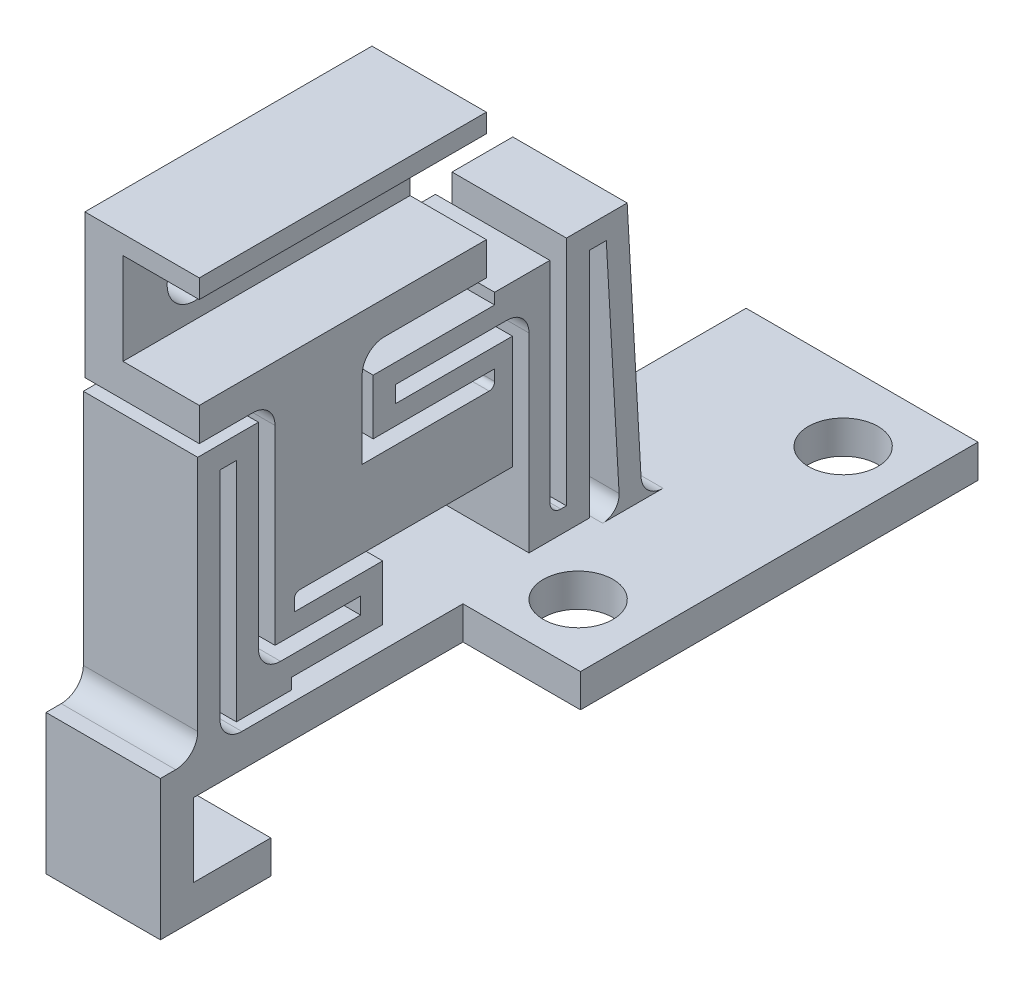
SolidWorks part; units mm, degrees
ref_plane "Front Plane" through (0, 0, 0) normal (0, 0, 1) x (1, 0, 0)
ref_plane "Top Plane" through (0, 0, 0) normal (0, 1, 0) x (1, 0, 0)
ref_plane "Right Plane" through (0, 0, 0) normal (1, 0, 0) x (0, 0, -1)
sketch "Sketch1" plane through (0, 0, 0) normal (1, 0, 0) x (0, 0, -1)
  line L0 (3.7437, -1.0669) -> (8.3687, -1.0669)
  line L1 (-4.6313, -1.0669) -> (-2.2011, -1.0669)
  line L2 (-4.6313, -1.0669) -> (-4.6313, 5.4331)
  line L3 (-4.6313, 5.4331) -> (8.3687, 5.4331)
  line L4 (8.3687, -1.0669) -> (8.3687, 5.4331)
  line L6 (-1.2011, -2.0669) -> (-1.2011, -10.6919)
  line L8 (2.7437, -2.0669) -> (2.7437, -5.5669)
  line L13 (-0.0761, -9.0669) -> (9.5489, -9.0669)
  line L14 (8.7437, -5.3169) -> (8.7437, -4.8169)
  line L16 (9.5489, -9.0669) -> (9.5489, -3.9419)
  line L17 (3.2437, -2.3169) -> (3.2437, -4.8169)
  line L20 (8.7437, -4.8169) -> (3.2437, -4.8169)
  line L25 (4.2437, -3.9419) -> (4.2437, -3.1919)
  line L26 (3.2437, -2.3169) -> (8.7437, -2.3169)
  line L28 (4.2437, -3.1919) -> (9.2989, -3.1919)
  line L32 (8.7437, -2.3169) -> (8.7437, -1.8169)
  line L33 (8.7437, -1.8169) -> (11.2437, -1.8169)
  line L35 (-1.2011, -10.6919) -> (2.6739, -10.6919)
  line L36 (2.6739, -10.6919) -> (2.6739, -11.4419)
  line L37 (2.6739, -11.4419) -> (-0.9511, -11.4419)
  line L40 (-2.9511, -12.8169) -> (-0.4511, -12.8169)
  line L41 (-0.4511, -12.8169) -> (-0.4511, -12.3169)
  line L42 (-0.4511, -12.3169) -> (3.6739, -12.3169)
  line L43 (3.6739, -12.3169) -> (3.6739, -9.8169)
  line L44 (3.6739, -9.8169) -> (-0.3261, -9.8169)
  line L45 (-0.3261, -9.8169) -> (-0.3261, -9.3169)
  line L48 (-1.9511, -10.4419) -> (-1.9511, -1.5669)
  line L50 (-2.9511, -12.8169) -> (-2.9511, -2.5669)
  line L51 (-1.9511, -1.5669) -> (-4.7011, -1.5669)
  line L53 (-2.9511, -2.5669) -> (-3.7011, -2.5669)
  line L56 (10.2989, -4.1919) -> (10.2989, -12.8169)
  line L58 (11.2437, -1.8169) -> (11.2437, -11.3169)
  line L59 (10.2989, -12.8169) -> (13.0489, -12.8169)
  line L61 (11.2437, -11.8169) -> (11.9937, -11.8169) construction
  line L65 (13.0489, -12.8169) -> (13.0489, -2.3169)
  line L67 (11.9937, -11.8169) -> (11.9937, -1.3169)
  line L69 (-4.7011, -1.5669) -> (-4.7011, -12.3169)
  line L71 (-3.7011, -2.5669) -> (-3.7011, -12.3169)
  line L72 (-4.7011, -13.3169) -> (-5.7011, -13.3169) construction
  line L76 (13.0489, -2.3169) -> (13.7989, -2.3169)
  line L78 (11.9937, -1.3169) -> (14.7437, -1.3169)
  line L80 (-4.6313, -14.8169) -> (15.4255, -14.8169)
  line L82 (13.63, -13.3169) -> (-2.7011, -13.3169)
  line L84 (4.2437, -3.9419) -> (9.5489, -3.9419)
  line L94 (8.4937, -5.5669) -> (2.7437, -5.5669)
  line L95 (13.7989, -2.3169) -> (14.3788, -12.5244)
  line L96 (4.2437, -2.3169) -> (4.2437, -3.1919) construction
  line L97 (4.2437, -3.9419) -> (4.2437, -4.8169) construction
  line L98 (2.6739, -9.8169) -> (2.6739, -10.6919) construction
  line L99 (2.6739, -11.4419) -> (2.6739, -12.3169) construction
  line L100 (8.7437, -4.8169) -> (8.7437, -5.5669) construction
  line L101 (-0.3261, -9.0669) -> (-0.3261, -9.8169)
  line L102 (14.7437, -1.3169) -> (15.4255, -13.3169)
  line L103 (11.9937, -11.8169) -> (11.7437, -11.8169)
  line L104 (-3.3261, -1.5669) -> (-3.3261, -2.5669) construction
  line L105 (15.4255, -13.3169) -> (15.4255, -14.8169)
  line L106 (-3.7011, -2.5669) -> (-4.7011, -2.5669) construction
  line L107 (-2.9511, -2.5669) -> (-1.9511, -2.5669) construction
  line L108 (-3.3261, -1.0669) -> (-3.3261, -1.5669) construction
  line L109 (3.2437, -3.5669) -> (2.7437, -3.5669) construction
  line L110 (3.6739, -12.3169) -> (3.6739, -13.3169) construction
  line L111 (-4.6313, -14.8169) -> (-4.8913, -14.8169)
  line L112 (-4.8913, -14.8169) -> (-4.8913, -18.1469)
  line L113 (-4.8913, -18.1469) -> (-1.3913, -18.1469)
  line L114 (-1.3913, -18.1469) -> (-1.3913, -19.6469)
  line L115 (-1.3913, -19.6469) -> (-6.3913, -19.6469)
  line L116 (-6.3913, -19.6469) -> (-6.3913, -13.3169)
  line L117 (-6.3913, -13.3169) -> (-5.7011, -13.3169)
  arc A0 (3.7437, -1.0669) -> (2.7437, -2.0669) centre (3.7437, -2.0669) ccw
  arc A1 (-2.2011, -1.0669) -> (-1.2011, -2.0669) centre (-2.2011, -2.0669) cw
  arc A2 (9.2989, -3.1919) -> (10.2989, -4.1919) centre (9.2989, -4.1919) cw
  arc A3 (-0.9511, -11.4419) -> (-1.9511, -10.4419) centre (-0.9511, -10.4419) cw
  arc A4 (-0.3261, -9.3169) -> (-0.0761, -9.0669) centre (-0.0761, -9.3169) cw
  arc A5 (8.7437, -5.3169) -> (8.4937, -5.5669) centre (8.4937, -5.3169) cw
  arc A6 (-2.7011, -13.3169) -> (-3.7011, -12.3169) centre (-2.7011, -12.3169) cw
  arc A7 (11.2437, -11.3169) -> (11.7437, -11.8169) centre (11.7437, -11.3169) ccw
  arc A10 (-5.7011, -13.3169) -> (-4.7011, -12.3169) centre (-5.7011, -12.3169) ccw
  arc A11 (14.3788, -12.5244) -> (13.63, -13.3169) centre (13.63, -12.5669) cw
  point P27 (14.4239, -13.3169)
  dimension "D4" = 1
  dimension "D14" = 0.25
  dimension "D18" = 1
  dimension "D20" = 0.5
  dimension "D21" = 0.75
  dimension "D2" = 13
  dimension "D3" = 6.5
  dimension "D5" = 13.75
  dimension "D6" = 20.25
  dimension "D13" = 1.5
  dimension "D25" = 5.5
  dimension "D27" = 2.5
  dimension "D32" = 10.75
  dimension "D33" = 0.875
  dimension "D37" = 0.5
  dimension "D39" = 2.5
  dimension "D41" = 4.125
  dimension "D42" = 1
  dimension "D11" = 0.75
  dimension "D17" = 1
  dimension "D12" = 1.25
  dimension "D15" = 11.75
  dimension "D16" = 1
  dimension "D22" = 0.75
  dimension "D7" = 11.5
  dimension "D8" = 2
  dimension "D9" = 2.75
  dimension "D19" = 93.252
  dimension "D23" = 1
  dimension "D26" = 3.33
  dimension "D28" = 1.5
  dimension "D29" = 1.5
  dimension "D30" = 5
  dimension "D31" = 0.75
  dimension "D10" = 1
extrude "Flexure Boss" add sketch "Sketch1" along normal blind 5.18
sketch "Sketch2" plane through (0, -14.8169, 0) normal (0, -1, 0) x (1, 0, 0)
  line L0 (0, 4.8913) -> (0, -15.4255) construction
  line L4 (-5.32, -7.3096) -> (-5.32, -25.3096)
  line L6 (5.18, 4.8913) -> (5.18, -15.4255) construction
  line L7 (-5.32, -25.3096) -> (5.18, -25.3096)
  line L12 (-5.32, -7.3096) -> (5.18, -7.3096)
  line L13 (5.18, -7.3096) -> (5.18, -25.3096)
  line L14 (5.18, 6.3913) -> (0, 6.3913) construction
  circle A0 centre (-2.435, -10.0887) radius 1.575
  circle A1 centre (-2.435, -22.0887) radius 1.575
  dimension "D1" = 16.48
  dimension "D2" = 5.32
  dimension "D3" = 12
  dimension "D4" = 3.15
  dimension "D5" = 2.435
  dimension "D6" = 18
  dimension "D8" = 7.3096
extrude "Mounting Plate Boss" add sketch "Sketch2" against normal blind 1.5
sketch "Sketch7" plane through (0, 0, 0) normal (-1, 0, 0) x (0, 0, 1)
  line L0 (-8.3687, 0.4331) -> (4.6313, 0.4331)
  line L1 (4.6313, 4.5831) -> (4.6313, 0.4331)
  line L2 (4.6313, 4.5831) -> (-8.3687, 4.5831)
  line L6 (-8.3687, 4.5831) -> (-8.3687, 0.4331)
  line L7 (4.6313, -1.0669) -> (4.6313, 5.4331) construction
  line L8 (-8.3687, -1.0669) -> (-8.3687, 5.4331) construction
  dimension "D1" = 1.5
  dimension "D2" = 4.15
extrude "Dovetail Connection Cut" cut sketch "Sketch7" against normal blind 3.455
hole_wizard "M3x0.5 Tapped Hole1" positions "Sketch11" profile "Sketch12" tap size "M3x0.5" standard "ANSI Metric" end condition up to next
sketch "Sketch11" plane through (5.18, 0, 0) normal (1, 0, 0) x (0, 0, -1)
  line L0 (-4.6313, 5.4331) -> (8.3687, 5.4331) construction
  line L1 (-4.6313, -1.0669) -> (-4.6313, 5.4331) construction
  line L2 (8.3687, -1.0669) -> (8.3687, 5.4331) construction
  point P0 (-1.3813, 2.4331)
  point P2 (5.1187, 2.4331)
  dimension "D1" = 3
  dimension "D2" = 3.25
  dimension "D3" = 3.25
sketch "Sketch12" plane through (5.18, 2.4331, 1.3813) normal (0, 1, 0) x (0, 0, -1)
  line L0 (0, 0) -> (0, 1.725)
  line L1 (0, 1.725) -> (1.25, 1.725)
  line L2 (1.25, 1.725) -> (1.25, 0)
  line L5 (1.25, 0) -> (0, 0)
  line L11 (0, -6.35) -> (0, 107.95) construction
  dimension "Thru Tap Drill Dia." = 2.5
  dimension "Thru Tap Drill Depth" = 1.725
cosmetic thread "Hole Thread1" parameters "D2"=3
cosmetic thread "Hole Thread2" parameters "D2"=3
mirror "Mirror2" about plane through (5.18, 0, 0) normal (1, 0, 0) of bodies 122 108
cosmetic thread "Hole Thread3" parameters "D2"=3
cosmetic thread "Hole Thread4" parameters "D2"=3
delete or keep bodies "Body-Delete/Keep 1" type delete bodies bodies 122
sketch "Sketch8" [suppressed] plane through (0, 0, 4.6313) normal (0, 0, 1) x (1, 0, 0)
  line L0 (5.18, -1.0669) -> (0, -1.0669) construction
  line L1 (1, 4.4331) -> (4.18, 4.4331)
  line L2 (1, 4.4331) -> (1, 0.4331)
  line L3 (1, 0.4331) -> (4.18, 0.4331)
  line L4 (4.18, 4.4331) -> (4.18, 0.4331)
  line L5 (5.18, -1.0669) -> (5.18, 5.4331) construction
  dimension "D1" = 1.5
  dimension "D2" = 1
  dimension "D3" = 4
  dimension "D4" = 3.18
extrude "Cut-Extrude1" [suppressed] cut sketch "Sketch8" against normal up to next
fillet "Fillet1" radius 1 1 edges at (7.77, -13.3169, -15.4255)
equation "\"FlexureExtrusionThickness\"=5.18"
equation "\"D1@Flexure Boss\"=\"FlexureExtrusionThickness\""
equation "\"MountingHoleEdgeDist\"= 3.57mm"
equation "\"FlexureGapDist\"= .75mm"
equation "\"D11@Sketch1\"=\"FlexureGapDist\""
equation "\"FlexureCornerThicknessOffset\"= .5mm"
equation "\"D37@Sketch1\"=\"FlexureCornerThicknessOffset\""
equation "\"FlexureCornerThicknessWidth\"= 2.5mm"
equation "\"D39@Sketch1\"=\"FlexureCornerThicknessWidth\""
equation "\"FlexureConnectorWidth\"= 2mm"
equation "\"FlexureConnectorThickness\"= 1mm"
equation "\"D17@Sketch1\"=\"FlexureConnectorThickness\""
equation "\"DribblerPlateHeightFromBase\"= 13.75mm"
equation "\"D5@Sketch1\"=\"DribblerPlateHeightFromBase\""
equation "\"FlexureOverallHeight\"= 13.5mm"
equation "\"D15@Sketch1\"=\"DribblerPlateHeightFromBase\" - \"FlexureBaseHeight\" - \"FlexureClearanceGapDist\""
equation "\"FlexureBaseHeight\"= 1.5mm"
equation "\"D13@Sketch1\"=\"FlexureBaseHeight\""
equation "\"FlexureClearanceGapDist\"= .5mm"
equation "\"D23@Sketch1\"=\"FlexureConnectorThickness\""
